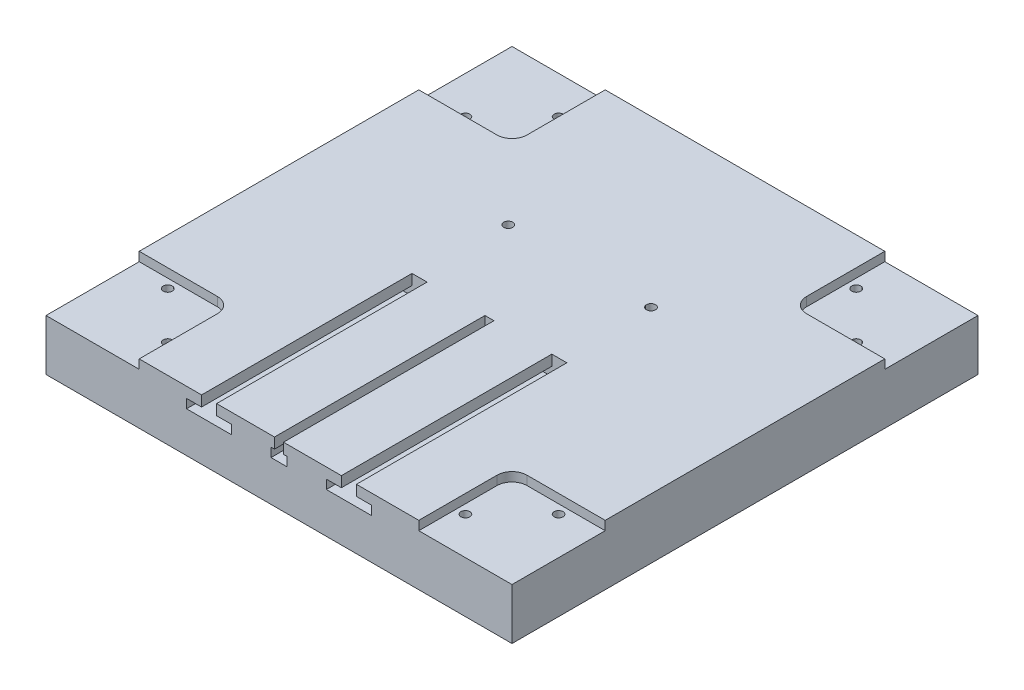
SolidWorks part; units mm, degrees
ref_plane "Front Plane" through (0, 0, 0) normal (0, 0, 1) x (1, 0, 0)
ref_plane "Top Plane" through (0, 0, 0) normal (0, 1, 0) x (1, 0, 0)
ref_plane "Right Plane" through (0, 0, 0) normal (1, 0, 0) x (0, 0, -1)
sketch "Sketch1" plane through (0, 0, 0) normal (0, 1, 0) x (1, 0, 0)
  line L0 (0, 77.5) -> (0, -77.5) construction
  line L1 (-77.5, 77.5) -> (77.5, 77.5)
  line L2 (-77.5, 77.5) -> (-77.5, -77.5)
  line L3 (-77.5, -77.5) -> (77.5, -77.5)
  line L4 (77.5, 77.5) -> (77.5, -77.5)
  line L5 (-77.5, 77.5) -> (77.5, -77.5) construction
  line L6 (-77.5, -77.5) -> (77.5, 77.5) construction
  line L15 (-77.5, 0) -> (77.5, 0) construction
  point P0 (0, 0)
  dimension "D1" = 155
  dimension "D2" = 155
extrude "Boss-Extrude2" add sketch "Sketch1" along normal blind 20
sketch "Sketch7" plane through (0, 20, 0) normal (0, 1, 0) x (1, 0, 0)
  line L0 (0, 77.5) -> (0, -77.5) construction
  line L1 (-77.5, 77.5) -> (-46.5, 77.5)
  line L2 (-77.5, 77.5) -> (-77.5, 46.5)
  line L3 (-77.5, 46.5) -> (-51.5, 46.5)
  line L4 (-46.5, 77.5) -> (-46.5, 51.5)
  line L5 (77.5, 77.5) -> (-77.5, 77.5) construction
  line L6 (-77.5, -77.5) -> (77.5, -77.5) construction
  line L7 (-77.5, 0) -> (77.5, 0) construction
  line L8 (-77.5, 77.5) -> (-77.5, -77.5) construction
  line L9 (77.5, -77.5) -> (77.5, 77.5) construction
  line L10 (77.5, 46.5) -> (51.5, 46.5)
  line L11 (46.5, 77.5) -> (46.5, 51.5)
  line L12 (77.5, 77.5) -> (46.5, 77.5)
  line L13 (77.5, 77.5) -> (77.5, 46.5)
  line L14 (77.5, -77.5) -> (77.5, -46.5)
  line L15 (77.5, -77.5) -> (46.5, -77.5)
  line L16 (46.5, -77.5) -> (46.5, -51.5)
  line L17 (77.5, -46.5) -> (51.5, -46.5)
  line L18 (-46.5, -77.5) -> (-46.5, -51.5)
  line L19 (-77.5, -46.5) -> (-51.5, -46.5)
  line L20 (-77.5, -77.5) -> (-77.5, -46.5)
  line L21 (-77.5, -77.5) -> (-46.5, -77.5)
  arc A0 (-51.5, 46.5) -> (-46.5, 51.5) centre (-51.5, 51.5) ccw
  arc A1 (51.5, 46.5) -> (46.5, 51.5) centre (51.5, 51.5) cw
  arc A2 (51.5, -46.5) -> (46.5, -51.5) centre (51.5, -51.5) ccw
  arc A3 (-51.5, -46.5) -> (-46.5, -51.5) centre (-51.5, -51.5) cw
  point P7 (-46.5, 46.5)
  point P38 (-46.5, -46.5)
  dimension "D3" = 5
  dimension "D1" = 31
  dimension "D2" = 31
extrude "Cut-Extrude6" cut sketch "Sketch7" against normal blind 3
sketch "Sketch8" plane through (0, 17, 0) normal (0, 1, 0) x (1, 0, 0)
  line L0 (-65, -52.5) -> (-65, -46.5) construction
  line L5 (-51.5, -46.5) -> (-77.5, -46.5) construction
  line L6 (-52.5, -65) -> (-46.5, -65) construction
  line L7 (-46.5, -77.5) -> (-46.5, -51.5) construction
  line L8 (-77.5, -77.5) -> (-46.5, -77.5) construction
  line L9 (-77.5, -46.5) -> (-77.5, -77.5) construction
  line L10 (0, 77.5) -> (0, -77.5) construction
  line L11 (46.5, 77.5) -> (-46.5, 77.5) construction
  line L12 (-46.5, -77.5) -> (46.5, -77.5) construction
  line L13 (52.5, -65) -> (46.5, -65) construction
  line L14 (65, -52.5) -> (65, -46.5) construction
  line L15 (-77.5, 0) -> (77.5, 0) construction
  line L16 (-77.5, 46.5) -> (-77.5, -46.5) construction
  line L17 (77.5, -46.5) -> (77.5, 46.5) construction
  circle A0 centre (-65, -49.5) radius 1.5
  circle A1 centre (-49.5, -65) radius 1.5
  circle A2 centre (49.5, -65) radius 1.5
  circle A3 centre (65, -49.5) radius 1.5
  circle A4 centre (49.5, 65) radius 1.5
  circle A5 centre (65, 49.5) radius 1.5
  circle A6 centre (-49.5, 65) radius 1.5
  circle A7 centre (-65, 49.5) radius 1.5
  dimension "D3" = 3
  dimension "D4" = 3
  dimension "D1" = 28
  dimension "D2" = 28
  dimension "D5" = 12.5
  dimension "D6" = 12.5
extrude "Cut-Extrude7" cut sketch "Sketch8" against normal up to next
sketch "Sketch9" plane through (0, 0, 77.5) normal (0, 0, 1) x (1, 0, 0)
  line L0 (0, 20) -> (0, 0) construction
  line L1 (-46.5, 20) -> (46.5, 20) construction
  line L2 (0, 10) -> (-46.5, 10) construction
  line L3 (-46.5, 20) -> (46.5, 20)
  line L4 (-46.5, 20) -> (-46.5, 0)
  line L5 (-46.5, 0) -> (46.5, 0)
  line L6 (46.5, 20) -> (46.5, 0)
  line L7 (-46.5, 20) -> (46.5, 0) construction
  line L8 (-46.5, 0) -> (46.5, 20) construction
  line L9 (-46.5, 10) -> (0, 10) construction
  line L10 (-20.75, 16.5) -> (-15.75, 16.5)
  line L11 (-23.25, 10) -> (-23.25, 20) construction
  line L12 (-30.75, 16.5) -> (-25.75, 16.5)
  line L13 (-30.75, 16.5) -> (-30.75, 13.5)
  line L14 (-30.75, 13.5) -> (-15.75, 13.5)
  line L15 (-15.75, 16.5) -> (-15.75, 13.5)
  line L16 (-30.75, 16.5) -> (-15.75, 13.5) construction
  line L17 (-30.75, 13.5) -> (-15.75, 16.5) construction
  line L18 (-25.75, 20) -> (-20.75, 20)
  line L19 (-25.75, 20) -> (-25.75, 16.5)
  line L21 (-20.75, 20) -> (-20.75, 16.5)
  line L22 (-25.75, 20) -> (-20.75, 16.5) construction
  line L23 (-25.75, 16.5) -> (-20.75, 20) construction
  line L24 (25.75, 16.5) -> (20.75, 20) construction
  line L25 (25.75, 20) -> (20.75, 16.5) construction
  line L26 (30.75, 13.5) -> (15.75, 16.5) construction
  line L27 (30.75, 16.5) -> (15.75, 13.5) construction
  line L28 (20.75, 20) -> (20.75, 16.5)
  line L29 (25.75, 20) -> (25.75, 16.5)
  line L30 (25.75, 20) -> (20.75, 20)
  line L31 (15.75, 16.5) -> (15.75, 13.5)
  line L32 (30.75, 13.5) -> (15.75, 13.5)
  line L33 (30.75, 16.5) -> (30.75, 13.5)
  line L34 (30.75, 16.5) -> (25.75, 16.5)
  line L35 (20.75, 16.5) -> (15.75, 16.5)
  line L36 (-15.75, 15) -> (15.75, 15) construction
  line L37 (1.5, 16.5) -> (2.65, 16.5)
  line L38 (-2.65, 16.5) -> (-1.5, 16.5)
  line L39 (-2.65, 16.5) -> (-2.65, 13.5)
  line L40 (-2.65, 13.5) -> (2.65, 13.5)
  line L41 (2.65, 16.5) -> (2.65, 13.5)
  line L42 (-2.65, 16.5) -> (2.65, 13.5) construction
  line L43 (-2.65, 13.5) -> (2.65, 16.5) construction
  line L44 (-1.5, 20) -> (1.5, 20)
  line L45 (-1.5, 20) -> (-1.5, 16.5)
  line L47 (1.5, 20) -> (1.5, 16.5)
  line L48 (-1.5, 20) -> (1.5, 16.5) construction
  line L49 (-1.5, 16.5) -> (1.5, 20) construction
  point P5 (0, 10)
  point P13 (-23.25, 15)
  point P19 (-23.25, 18.25)
  point P32 (23.25, 18.25)
  point P33 (23.25, 15)
  point P36 (0, 15)
  point P41 (0, 18.25)
  dimension "D1" = 93
  dimension "D2" = 20
  dimension "D3" = 3
  dimension "D4" = 15
  dimension "D5" = 3.5
  dimension "D6" = 5
  dimension "D7" = 5.3
  dimension "D8" = 3
  dimension "D9" = 3.5
  dimension "D10" = 3
extrude "Cut-Extrude8" cut sketch "Sketch9" against normal blind 70 contours L21 L3 L19 L12 L13 L14 L15 L10 | L28 L35 L31 L32 L33 L34 L29 L3 | L38 L45 L44 L47 L37 L41 L40 L39
sketch "Sketch10" plane through (0, 20, 0) normal (0, 1, 0) x (1, 0, 0)
  line L0 (46.5, 77.5) -> (-46.5, 77.5) construction
  line L2 (77.5, -46.5) -> (77.5, 46.5) construction
  circle A0 centre (-23.75, 22.5) radius 1.5
  circle A1 centre (23.75, 22.5) radius 1.5
  point P2 (0, 77.5)
  point P7 (0, 22.5)
  dimension "D1" = 3
  dimension "D2" = 3
  dimension "D3" = 47.5
  dimension "D4" = 55
  dimension "D5" = 53.75
extrude "Cut-Extrude9" cut sketch "Sketch10" against normal up to next
